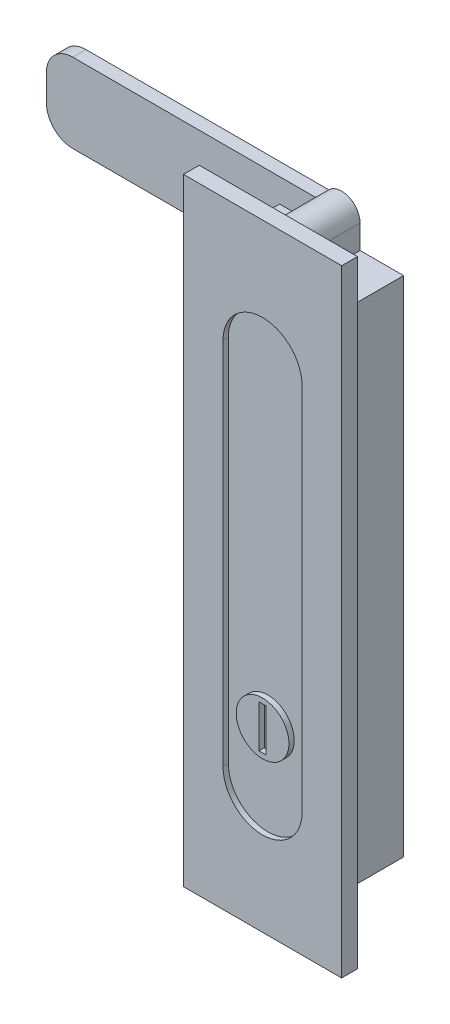
SolidWorks part; units mm, degrees
ref_plane "前视基准面" through (0, 0, 0) normal (0, 0, 1) x (1, 0, 0)
ref_plane "上视基准面" through (0, 0, 0) normal (0, 1, 0) x (1, 0, 0)
ref_plane "右视基准面" through (0, 0, 0) normal (1, 0, 0) x (0, 0, -1)
sketch "草图1" plane through (0, 0, 0) normal (0, 0, 1) x (1, 0, 0)
  line L1 (-15, -58.5) -> (15, -58.5)
  line L2 (-15, -58.5) -> (-15, 58.5)
  line L3 (-15, 58.5) -> (15, 58.5)
  line L4 (15, -58.5) -> (15, 58.5)
  line L5 (-15, -58.5) -> (15, 58.5) construction
  line L6 (-15, 58.5) -> (15, -58.5) construction
  point P0 (0, 0)
  dimension "D1" = 30
  dimension "D2" = 117
extrude "凸台-拉伸1" add sketch "草图1" along normal blind 3
sketch "草图2" plane through (0, 0, 3) normal (0, 0, 1) x (1, 0, 0)
  line L0 (0, -35) -> (0, 35) construction
  line L1 (-7.5, -35) -> (-7.5, 35)
  line L2 (7.5, -35) -> (7.5, 35)
  arc A0 (-7.5, -35) -> (7.5, -35) centre (0, -35) ccw
  arc A1 (7.5, 35) -> (-7.5, 35) centre (0, 35) ccw
  circle A2 centre (0, -25) radius 5
  point P2 (0, 0)
  dimension "D3" = 25
  dimension "10" = 10
  dimension "D1" = 15
  dimension "D2" = 70
extrude "切除-拉伸1" cut sketch "草图2" against normal blind 1
sketch "草图3" plane through (0, 0, 3) normal (0, 0, 1) x (1, 0, 0)
  line L1 (-0.6757, -29.0292) -> (0.6757, -29.0292)
  line L2 (-0.6757, -29.0292) -> (-0.6757, -20.9708)
  line L3 (-0.6757, -20.9708) -> (0.6757, -20.9708)
  line L4 (0.6757, -29.0292) -> (0.6757, -20.9708)
  line L5 (-0.6757, -29.0292) -> (0.6757, -20.9708) construction
  line L6 (-0.6757, -20.9708) -> (0.6757, -29.0292) construction
  point P0 (0, -25)
extrude "切除-拉伸2" cut sketch "草图3" against normal blind 1
sketch "草图4" plane through (0, 0, 0) normal (0, 0, -1) x (-1, 0, 0)
  line L0 (0, -52.25) -> (0, 52.25) construction
  line L1 (-11.75, -47.75) -> (11.75, -47.75)
  line L2 (-11.75, -47.75) -> (-11.75, 47.75)
  line L3 (-11.75, 47.75) -> (11.75, 47.75)
  line L4 (11.75, -47.75) -> (11.75, 47.75)
  line L5 (-11.75, -47.75) -> (11.75, 47.75) construction
  line L6 (-11.75, 47.75) -> (11.75, -47.75) construction
  line L7 (-3.5, -52.25) -> (-3.5, 52.25)
  line L8 (3.5, -52.25) -> (3.5, 52.25)
  arc A0 (-3.5, -52.25) -> (3.5, -52.25) centre (0, -52.25) ccw
  arc A1 (3.5, 52.25) -> (-3.5, 52.25) centre (0, 52.25) ccw
  point P0 (0, 0)
  point P8 (0, 0)
  dimension "D1" = 95.5
  dimension "23.5" = 23.5
  dimension "D2" = 7
  dimension "D3" = 104.5
extrude "凸台-拉伸2" add sketch "草图4" along normal blind 12 contours L1 L7 L3 L2 | L1 L8 L3 L7 | L8 A1 L7 L3 | L8 L1 L4 L3 | L7 A0 L8 L1
sketch "草图5" plane through (0, 0, -12) normal (0, 0, -1) x (-1, 0, 0)
  line L0 (0, 52.25) -> (51, 52.25)
  line L1 (56, 47.25) -> (56, 42.25)
  line L2 (51, 37.25) -> (0, 37.25)
  line L3 (0, 37.25) -> (0, 52.25)
  arc A0 (51, 37.25) -> (56, 42.25) centre (51, 42.25) ccw
  arc A1 (56, 47.25) -> (51, 52.25) centre (51, 47.25) ccw
  point P7 (56, 37.25)
  point P10 (56, 52.25)
  dimension "D2" = 5
  dimension "D1" = 15
  dimension "56" = 56
extrude "凸台-拉伸3" add sketch "草图5" along normal blind 2.5
